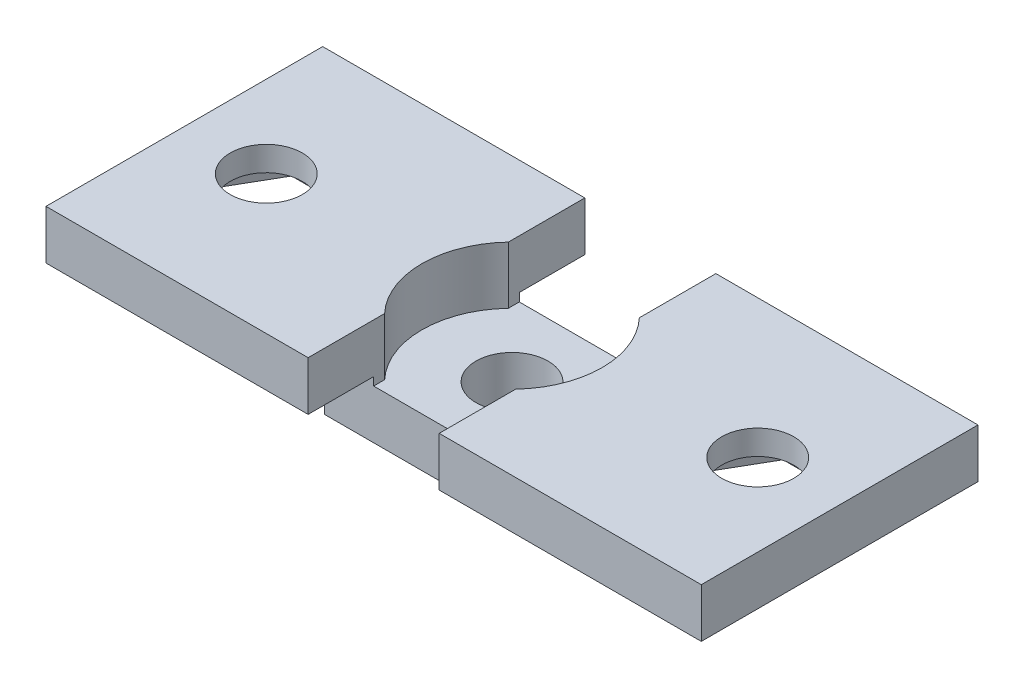
SolidWorks part; units mm, degrees
ref_plane "Front Plane" through (0, 0, 0) normal (0, 0, 1) x (1, 0, 0)
ref_plane "Top Plane" through (0, 0, 0) normal (0, 1, 0) x (1, 0, 0)
ref_plane "Right Plane" through (0, 0, 0) normal (1, 0, 0) x (0, 0, -1)
sketch "Sketch1" plane through (0, 0, 0) normal (0, 1, 0) x (1, 0, 0)
  line L0 (-15, 0) -> (0, 0) construction
  line L1 (20, -4.445) -> (-20, -4.445)
  line L2 (20, -4.445) -> (20, 4.445)
  line L3 (20, 4.445) -> (-20, 4.445)
  line L4 (-20, -4.445) -> (-20, 4.445)
  line L5 (20, -4.445) -> (-20, 4.445) construction
  line L6 (20, 4.445) -> (-20, -4.445) construction
  line L7 (0, 0) -> (15, 0) construction
  circle A0 centre (0, 0) radius 2.2
  circle A1 centre (-15, 0) radius 2.2
  circle A2 centre (15, 0) radius 2.2
  point P0 (0, 0)
  dimension "D1" = 4.4
  dimension "D2" = 15
  dimension "D3" = 8.89
  dimension "D4" = 40
extrude "Boss-Extrude1" add sketch "Sketch1" along normal blind 6.5
sketch "Sketch2" plane through (0, 0, 4.445) normal (0, 0, 1) x (1, 0, 0)
  line L0 (-4, 6.5) -> (-4, 3)
  line L1 (-20, 6.5) -> (20, 6.5) construction
  line L2 (-4, 3) -> (4, 3)
  line L3 (4, 3) -> (4, 6.5)
  line L4 (4, 6.5) -> (-4, 6.5)
  line L5 (-20, 3.5) -> (-7, 3.5)
  line L6 (-20, 6.5) -> (-20, 0) construction
  line L7 (-7, 3.5) -> (-7, 0)
  line L8 (-20, 0) -> (20, 0) construction
  line L9 (-7, 0) -> (-20, 0)
  line L10 (-20, 0) -> (-20, 3.5)
  line L11 (7, 3.5) -> (20, 3.5)
  line L12 (20, 6.5) -> (20, 0) construction
  line L13 (20, 3.5) -> (20, 0)
  line L14 (20, 0) -> (7, 0)
  line L15 (7, 0) -> (7, 3.5)
  point P22 (0, 6.5)
  dimension "D1" = 3
  dimension "D2" = 13
  dimension "D3" = 3.5
  dimension "D4" = 8
extrude "Cut-Extrude1" cut sketch "Sketch2" against normal up to surface (8.89 mm away) up to face at (0, 3.25, -4.445)
sketch "Sketch3" plane through (0, 3, 0) normal (0, 1, 0) x (1, 0, 0)
  circle A0 centre (0, 0) radius 5.5
  dimension "D1" = 11
extrude "Cut-Extrude2" cut sketch "Sketch3" along normal up to surface (3.5 mm away) up to face at (-12, 6.5, 0)
sketch "Sketch4" plane through (0, 3.5, 0) normal (0, -1, 0) x (-1, 0, 0)
  line L1 (12.8927, 3.65) -> (10.7853, 0)
  line L2 (10.7853, 0) -> (12.8927, -3.65)
  line L3 (12.8927, -3.65) -> (17.1073, -3.65)
  line L4 (17.1073, -3.65) -> (19.2147, 0)
  line L5 (19.2147, 0) -> (17.1073, 3.65)
  line L6 (17.1073, 3.65) -> (12.8927, 3.65)
  line L7 (-17.1073, 3.65) -> (-19.2147, 0)
  line L8 (-19.2147, 0) -> (-17.1073, -3.65)
  line L9 (-17.1073, -3.65) -> (-12.8927, -3.65)
  line L10 (-12.8927, -3.65) -> (-10.7853, 0)
  line L11 (-10.7853, 0) -> (-12.8927, 3.65)
  line L12 (-12.8927, 3.65) -> (-17.1073, 3.65)
  line L13 (7, -4.445) -> (20, -4.445) construction
  line L14 (-20, -4.445) -> (-7, -4.445) construction
  circle A0 centre (15, 0) radius 3.65 construction
  circle A1 centre (-15, 0) radius 3.65 construction
  dimension "D1" = 7.3
extrude "Cut-Extrude3" cut sketch "Sketch4" against normal blind 1.5 contours L1 L2 L3 L4 L5 L6 | L7 L8 L9 L10 L11 L12
sketch "Sketch6" plane through (0, 0, 4.445) normal (0, 0, 1) x (1, 0, 0)
  line L1 (-20, 3.5) -> (-4, 3.5)
  line L2 (-20, 3.5) -> (-20, 6.5)
  line L3 (-20, 6.5) -> (-4, 6.5)
  line L4 (-4, 3.5) -> (-4, 6.5)
  line L5 (4, 6.5) -> (20, 6.5)
  line L6 (4, 6.5) -> (4, 3.5)
  line L7 (4, 3.5) -> (20, 3.5)
  line L8 (20, 6.5) -> (20, 3.5)
extrude "Boss-Extrude2" add sketch "Sketch6" along normal blind 4
mirror "Mirror1" about plane through (0, 0, 0) normal (0, 0, 1) of "Boss-Extrude2"
